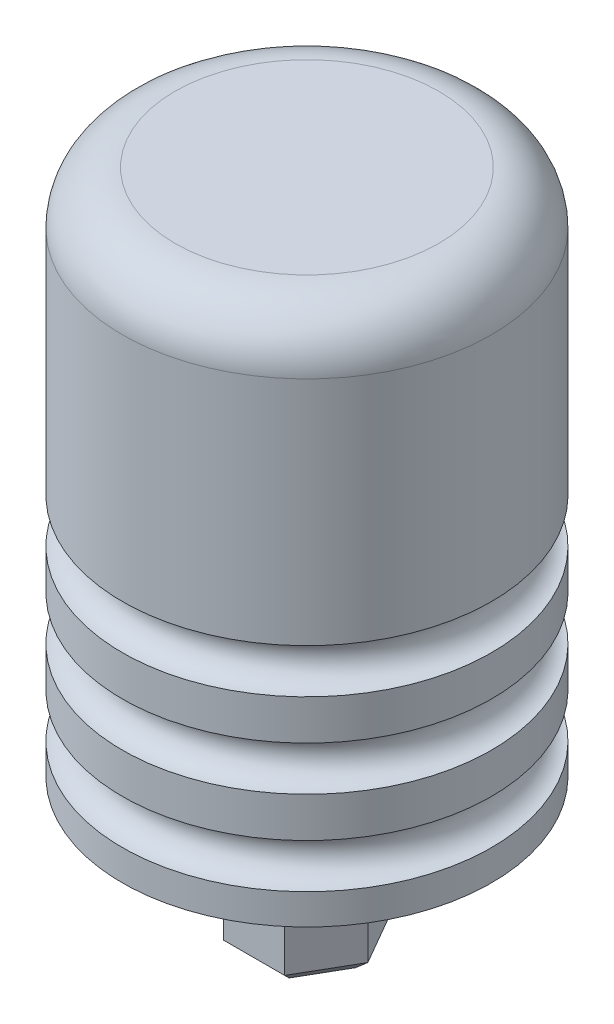
SolidWorks part; units mm, degrees
material "ABS"
ref_plane "Front Plane" through (0, 0, 0) normal (0, 0, 1) x (1, 0, 0)
ref_plane "Top Plane" through (0, 0, 0) normal (0, 1, 0) x (1, 0, 0)
ref_plane "Right Plane" through (0, 0, 0) normal (1, 0, 0) x (0, 0, -1)
sketch "Sketch1" plane through (0, 0, 0) normal (0, 0, 1) x (1, 0, 0)
  line L0 (0, 0) -> (0, 63.5)
  line L1 (0, 63.5) -> (15.875, 63.5)
  line L2 (22.225, 57.15) -> (22.225, 29.337)
  line L3 (22.225, 0) -> (0, 0)
  line L4 (22.225, 24.003) -> (22.225, 19.177)
  line L5 (22.225, 13.843) -> (22.225, 9.017)
  line L6 (22.225, 3.683) -> (22.225, 0)
  arc A0 (22.225, 9.017) -> (22.225, 3.683) centre (22.225, 6.35) ccw
  arc A1 (22.225, 19.177) -> (22.225, 13.843) centre (22.225, 16.51) ccw
  arc A2 (22.225, 29.337) -> (22.225, 24.003) centre (22.225, 26.67) ccw
  arc A3 (15.875, 63.5) -> (22.225, 57.15) centre (15.875, 57.15) cw
  point P13 (22.225, 63.5)
  dimension "D3" = 5.334
  dimension "D7" = 6.35
  dimension "D1" = 22.225
  dimension "D2" = 63.5
  dimension "D4" = 10.16
  dimension "D5" = 10.16
  dimension "D6" = 6.35
revolve "Revolve1" add sketch "Sketch1" angle 360 about L0
sketch "Sketch2" plane through (0, 0, 0) normal (0, -1, 0) x (-1, 0, 0)
  line L1 (-7.3323, 0) -> (-3.6662, -6.35)
  line L2 (-3.6662, -6.35) -> (3.6662, -6.35)
  line L3 (3.6662, -6.35) -> (7.3323, 0)
  line L4 (7.3323, 0) -> (3.6662, 6.35)
  line L5 (3.6662, 6.35) -> (-3.6662, 6.35)
  line L6 (-3.6662, 6.35) -> (-7.3323, 0)
  circle A0 centre (0, 0) radius 6.35 construction
extrude "Boss-Extrude1" add sketch "Sketch2" along normal blind 17.018
fillet "Fillet1" radius 3.81 6 edges at (0, 0, -6.35) (-5.4993, 0, -3.175) (-5.4993, 0, 3.175) (0, 0, 6.35) (5.4993, 0, 3.175) (5.4993, 0, -3.175)
chamfer "Chamfer1" distance 1.27 angle 45 6 edges at (5.4993, -17.018, -3.175) (0, -17.018, -6.35) (-5.4993, -17.018, -3.175) (-5.4993, -17.018, 3.175) (0, -17.018, 6.35) (5.4993, -17.018, 3.175)
